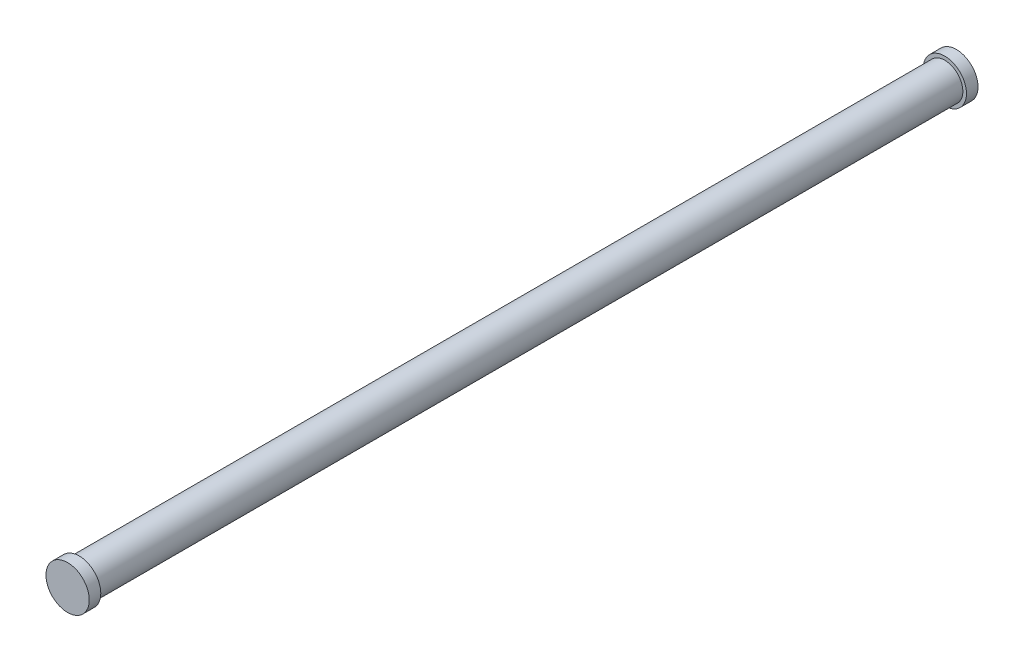
SolidWorks part; units mm, degrees
ref_plane "Alzado" through (0, 0, 0) normal (0, 0, 1) x (1, 0, 0)
ref_plane "Planta" through (0, 0, 0) normal (0, 1, 0) x (1, 0, 0)
ref_plane "Vista lateral" through (0, 0, 0) normal (1, 0, 0) x (0, 0, -1)
sketch "Croquis1" plane through (0, 0, 0) normal (0, 0, 1) x (1, 0, 0)
  circle A0 centre (0, 0) radius 12.5
  dimension "D1" = 25
extrude "Saliente-Extruir1" add sketch "Croquis1" against normal blind 600
sketch "Croquis2" plane through (0, 0, 0) normal (0, 0, 1) x (1, 0, 0)
  circle A0 centre (0, 0) radius 15
  dimension "30" = 30
extrude "Saliente-Extruir2" add sketch "Croquis2" along normal blind 8
ref_plane "Plano1" through (0, 0, -300) normal (0, 0, 1) x (1, 0, 0)
mirror "Simetría1" about plane through (0, 0, -300) normal (0, 0, 1) of "Saliente-Extruir2"
